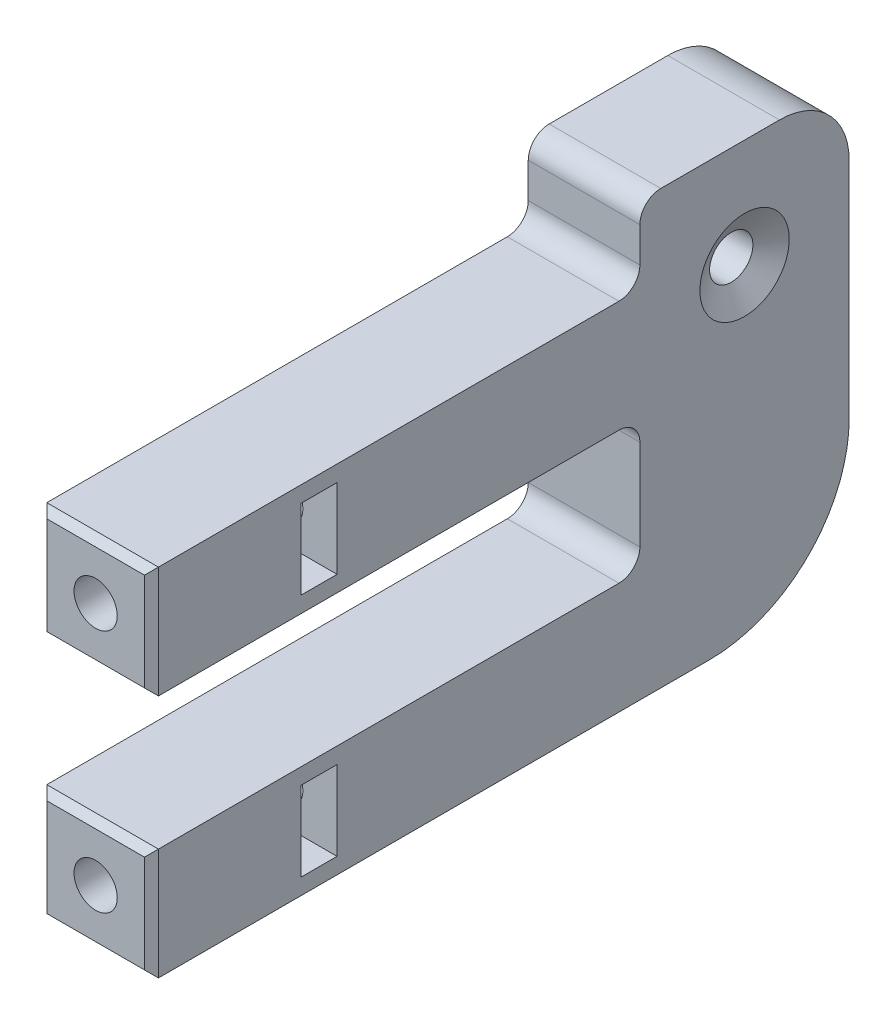
SolidWorks part; units mm, degrees
ref_plane "Front Plane" through (0, 0, 0) normal (0, 0, 1) x (1, 0, 0)
ref_plane "Top Plane" through (0, 0, 0) normal (0, 1, 0) x (1, 0, 0)
ref_plane "Right Plane" through (0, 0, 0) normal (1, 0, 0) x (0, 0, -1)
sketch "Sketch1" plane through (0, 0, 0) normal (1, 0, 0) x (0, 0, -1)
  line L0 (0, 0) -> (50, 0)
  line L1 (50, 0) -> (50, 31)
  line L2 (50, 31) -> (35, 31)
  line L3 (35, 31) -> (35, 25.5)
  line L4 (35, 25.5) -> (0, 25.5)
  line L5 (0, 25.5) -> (0, 17.5)
  line L6 (0, 17.5) -> (35, 17.5)
  line L7 (35, 17.5) -> (35, 8)
  line L8 (35, 8) -> (0, 8)
  line L9 (0, 8) -> (0, 0)
  line L10 (0, 21.5) -> (10, 21.5) construction
  line L11 (0, 4) -> (10, 4) construction
  line L12 (10, 21.5) -> (10, 4) construction
  line L13 (10, 12.75) -> (42.5, 12.75) construction
  line L14 (42.5, 12.75) -> (42.5, 23.25) construction
  circle A0 centre (42.5, 23.25) radius 1.55
  dimension "D12" = 3.1
  dimension "D1" = 15
  dimension "D2" = 8
  dimension "D3" = 8
  dimension "D4" = 10
  dimension "D5" = 10
  dimension "D6" = 17.5
  dimension "D7" = 35
  dimension "D8" = 50
  dimension "D9" = 32.5
  dimension "D10" = 10.5
  dimension "D11" = 31
extrude "Boss-Extrude1" add sketch "Sketch1" along normal blind 8
sketch "Sketch2" plane through (8, 0, 0) normal (1, 0, 0) x (0, 0, -1)
  circle A0 centre (42.5, 23.25) radius 3.2
  dimension "D1" = 6.4
extrude "Cut-Extrude1" cut sketch "Sketch2" against normal blind 1.5 draft 60
sketch "Sketch3" plane through (0, 0, 0) normal (-1, 0, 0) x (0, 0, 1)
  circle A0 centre (-42.5, 23.25) radius 1.55
  circle A1 centre (-42.5, 23.25) radius 2.5
  dimension "D1" = 3.1
  dimension "D2" = 5
extrude "Boss-Extrude2" add sketch "Sketch3" along normal blind 0.75
sketch "Sketch4" plane through (0, 0, 0) normal (0, 0, 1) x (1, 0, 0)
  line L0 (0, 25.5) -> (8, 17.5) construction
  line L1 (8, 8) -> (0, 0) construction
  circle A0 centre (4, 21.5) radius 1.55
  circle A1 centre (4, 4) radius 1.55
  dimension "D1" = 3.1
  dimension "D2" = 3.1
extrude "Cut-Extrude2" cut sketch "Sketch4" against normal blind 20
sketch "Sketch5" plane through (0, 0, 0) normal (-1, 0, 0) x (0, 0, 1)
  line L0 (0, 21.5) -> (-12, 21.5) construction
  line L1 (0, 25.5) -> (0, 17.5) construction
  line L2 (0, 4) -> (-12, 4) construction
  line L3 (0, 8) -> (0, 0) construction
  line L5 (-13.3, 18.65) -> (-10.7, 18.65)
  line L6 (-13.3, 18.65) -> (-13.3, 24.35)
  line L7 (-13.3, 24.35) -> (-10.7, 24.35)
  line L8 (-10.7, 18.65) -> (-10.7, 24.35)
  line L9 (-13.3, 18.65) -> (-10.7, 24.35) construction
  line L10 (-13.3, 24.35) -> (-10.7, 18.65) construction
  line L11 (-13.3, 1.15) -> (-10.7, 1.15)
  line L12 (-13.3, 1.15) -> (-13.3, 6.85)
  line L13 (-13.3, 6.85) -> (-10.7, 6.85)
  line L14 (-10.7, 1.15) -> (-10.7, 6.85)
  line L15 (-13.3, 1.15) -> (-10.7, 6.85) construction
  line L16 (-13.3, 6.85) -> (-10.7, 1.15) construction
  dimension "D1" = 12
  dimension "D2" = 12
  dimension "D3" = 2.6
  dimension "D4" = 5.7
  dimension "D5" = 2.6
  dimension "D6" = 5.7
extrude "Cut-Extrude3" cut sketch "Sketch5" against normal through all
fillet "Fillet2" radius 1.5 4 edges at (4, 31, -35) (4, 25.5, -35) (4, 8, -35) (4, 17.5, -35)
fillet "Fillet3" radius 5 1 edges at (4, 31, -50)
fillet "Fillet4" radius 10 1 edges at (4, 0, -50)
chamfer "Chamfer1" distance 0.5 angle 45 8 edges at (0, 4, 0) (4, 0, 0) (8, 4, 0) (4, 8, 0) (4, 17.5, 0) (0, 21.5, 0) (8, 21.5, 0) (4, 25.5, 0)
